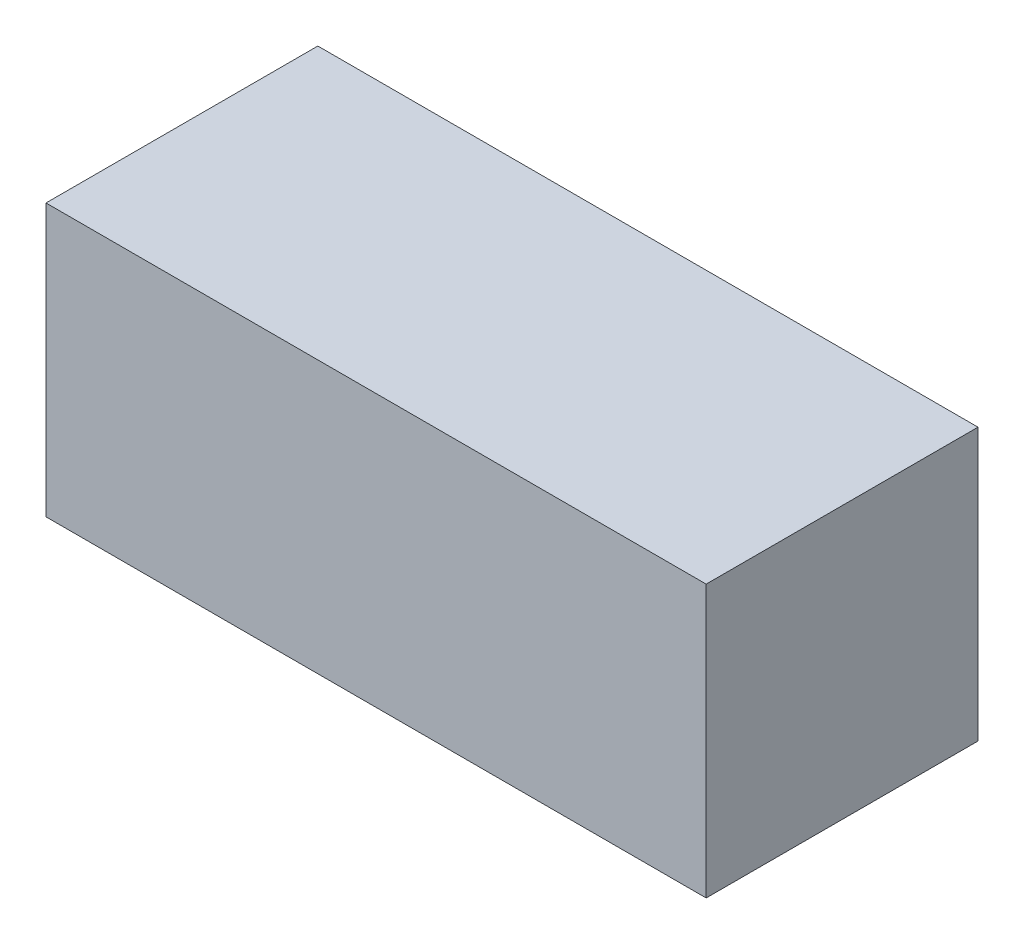
SolidWorks part; units mm, degrees
ref_plane "Front Plane" through (0, 0, 0) normal (0, 0, 1) x (1, 0, 0)
ref_plane "Top Plane" through (0, 0, 0) normal (0, 1, 0) x (1, 0, 0)
ref_plane "Right Plane" through (0, 0, 0) normal (1, 0, 0) x (0, 0, -1)
sketch "Эскиз1" plane through (0, 0, 0) normal (0, 0, 1) x (1, 0, 0)
  line L1 (-85, -35) -> (85, -35)
  line L2 (-85, -35) -> (-85, 35)
  line L3 (-85, 35) -> (85, 35)
  line L4 (85, -35) -> (85, 35)
  line L5 (-85, -35) -> (85, 35) construction
  line L6 (-85, 35) -> (85, -35) construction
  point P0 (0, 0)
  dimension "D1" = 70
  dimension "D2" = 170
extrude "Бобышка-Вытянуть1" add sketch "Эскиз1" along normal mid plane 70
